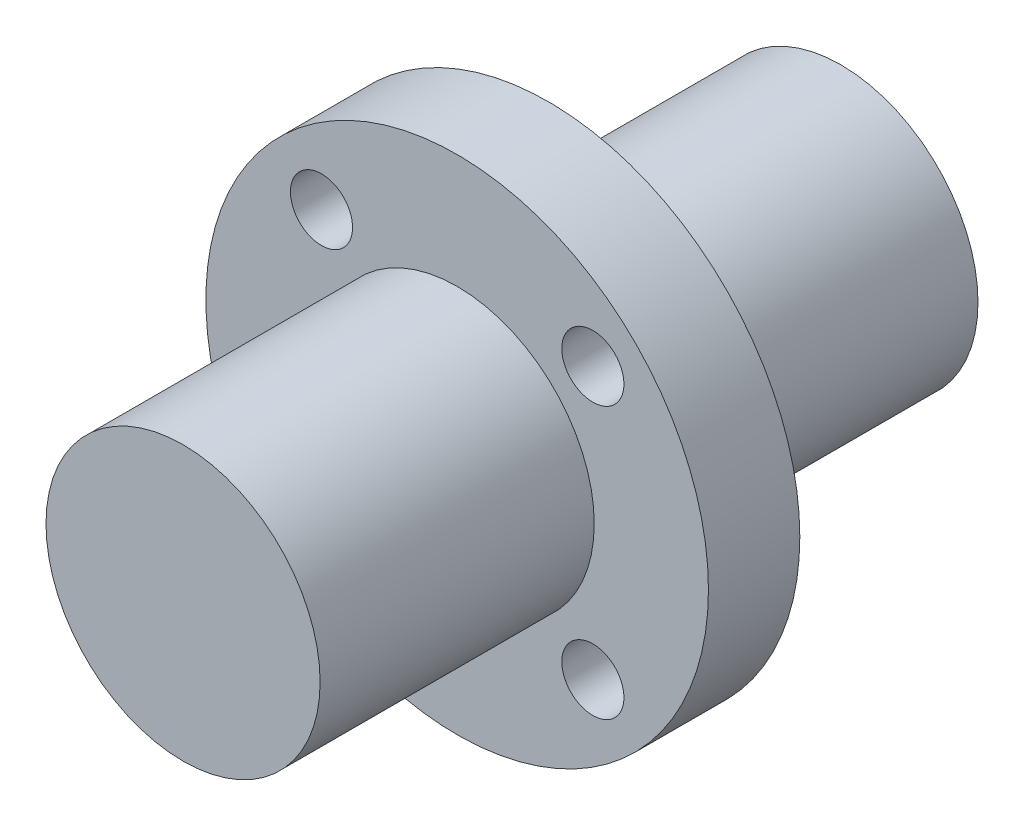
SolidWorks part; units mm, degrees
material "A6061"
ref_plane "前视基准面" through (0, 0, 0) normal (0, 0, 1) x (1, 0, 0)
ref_plane "上视基准面" through (0, 0, 0) normal (0, 1, 0) x (1, 0, 0)
ref_plane "右视基准面" through (0, 0, 0) normal (1, 0, 0) x (0, 0, -1)
sketch "草图1" plane through (0, 0, 0) normal (0, 0, 1) x (1, 0, 0)
  line L0 (-14.8492, 14.8492) -> (0, 0) construction
  line L1 (0, 0) -> (0, 30.9047) construction
  circle A0 centre (0, 0) radius 77.5 construction
  circle A1 centre (0, 0) radius 27.5
  circle A2 centre (0, 77.5) radius 4
  circle A3 centre (67.117, 38.75) radius 4
  circle A4 centre (67.117, -38.75) radius 4
  circle A5 centre (0, -77.5) radius 4
  circle A6 centre (-67.117, -38.75) radius 4
  circle A7 centre (-67.117, 38.75) radius 4
  circle A8 centre (0, 77.5) radius 5.5 construction
  circle A9 centre (-14.8492, 14.8492) radius 3
  circle A10 centre (0, 0) radius 21 construction
  circle A11 centre (14.8492, 14.8492) radius 3
  circle A12 centre (14.8492, -14.8492) radius 3
  circle A13 centre (-14.8492, -14.8492) radius 3
  point P19 (0, 0)
  point P30 (0, 0)
  dimension "D1" = 155
  dimension "D2" = 55
  dimension "D3" = 8
  dimension "D5" = 11
  dimension "D6" = 42
  dimension "D7" = 6
  dimension "D8" = 45
  dimension "D4" = 6
  dimension "D9" = 4
extrude "凸台-拉伸1" add sketch "草图1" along normal blind 10 contours A1 A13 A12 A11 A9
hole_wizard "M8 螺纹孔1" positions "草图4" profile "草图5" tap size "M8" standard "GB" end condition through all
sketch "草图4" plane through (0, 0, 0) normal (0, 0, 1) x (1, 0, 0)
  point P0 (-14.8492, 14.8492)
  point P3 (14.8492, 14.8492)
  point P6 (14.8492, -14.8492)
  point P9 (-14.8492, -14.8492)
sketch "草图5" plane through (-14.8492, 14.8492, 0) normal (1, 0, 0) x (0, 1, 0)
  line L0 (0, 0) -> (0, 10)
  line L1 (0, 10) -> (3.4, 10)
  line L2 (3.4, 10) -> (3.4, 0)
  line L5 (3.4, 0) -> (0, 0)
  line L11 (0, -6.35) -> (0, 107.95) construction
  dimension "通孔螺纹孔钻头直径" = 6.8
  dimension "通孔螺纹孔钻头深度" = 10
cosmetic thread "孔螺蚊线5" parameters "D2"=8
cosmetic thread "孔螺蚊线6" parameters "D2"=8
cosmetic thread "孔螺蚊线7" parameters "D2"=8
cosmetic thread "孔螺蚊线8" parameters "D2"=8
sketch "草图6" plane through (0, 0, 0) normal (0, 0, -1) x (-1, 0, 0)
  circle A0 centre (0, 0) radius 15
  dimension "D1" = 30
extrude "凸台-拉伸2" add sketch "草图6" along normal blind 32 and the other way blind 40
